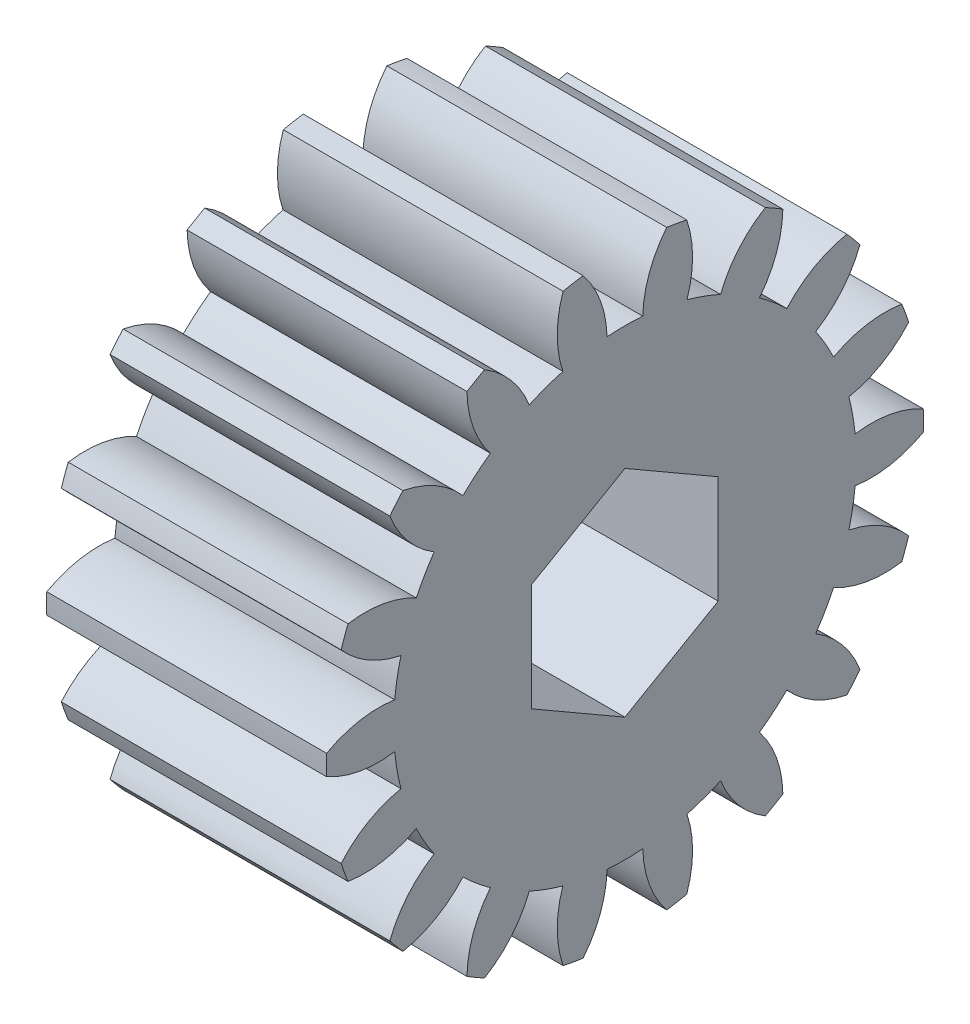
SolidWorks part; units mm, degrees
ref_plane "Plane1" through (0, 0, 0) normal (0, 0, 1) x (1, 0, 0)
ref_plane "Plane2" through (0, 0, 0) normal (0, 1, 0) x (1, 0, 0)
ref_plane "Plane3" through (0, 0, 0) normal (1, 0, 0) x (0, 0, -1)
other "Configuration Table"
sketch "HoldingSke" plane through (0, 0, 0) normal (0, 1, 0) x (1, 0, 0)
  line L0 (0, 0) -> (1.1888, -0.3863)
  line L1 (-15, 0) -> (100, 0) construction
  line L2 (0, 0) -> (-2.1039, 2.3779)
  line L3 (0, 0) -> (-11.863, 4.5341)
  line L4 (0, 0) -> (8.2133, 2.6687)
  line L5 (0, 0) -> (-46.8476, -17.4728)
  line L6 (0, 0) -> (-6.2172, -4.1948)
  line L7 (-2.1039, 2.3779) -> (8.6586, 51.2059)
  line L8 (-76.2, 54.61) -> (-75.3, 54.61)
  line L9 (-67.7845, 28.3722) -> (-49.3413, 33.142)
  line L10 (-76.2, 71.12) -> (104.1128, 71.12)
  line L11 (0, 0) -> (-7.5, 0)
  line L12 (-76.2, 101.6) -> (-76.17, 101.6)
  line L13 (24.9733, 27.94) -> (52.9518, 28.4284)
  line L14 (24.9733, 27.94) -> (24.9743, 27.94)
  line L15 (24.9733, 27.94) -> (100.4006, 29.5858)
  line L16 (-63.627, -0.8) -> (-12.827, -0.8)
  circle A0 centre (0, 0) radius 2.5
  circle A1 centre (0, 0) radius 6.199
  circle A2 centre (0, 0) radius 37.5
  circle A3 centre (0, 0) radius 2.5
  dimension "MHD" = 12.398
  dimension "Hub_dia" = 75
  dimension "Bore" = 5
  dimension "MBD" = 5
  dimension "Num_teeth" = 18
  dimension "Pitch" = 1.25
  dimension "Overall_len" = 50
  dimension "Show_teeth" = 18
  dimension "Thickness" = 7.5
  dimension "OAL" = 50.0001
  dimension "T_dim" = 0.9
  dimension "Ap" = 14.5
  dimension "H" = 19.05
  dimension "Pitch_radius" = 180.3128
  dimension "Width" = 7.5
  dimension "Backlash" = 0.03
  dimension "Addendum_fac" = 1
  dimension "Dedendum_fac" = 1.25
  dimension "Clearance_fac" = 0.25
  dimension "Dedendum_add" = 0.001
  dimension "Module" = 0.8
sketch "BasProSke" plane through (0, 0, 0) normal (0, 1, 0) x (1, 0, 0)
  line L0 (-10, 0) -> (60, 0) construction
  line L1 (0, 0) -> (0, 8)
  line L2 (0, 0) -> (7.5, 0)
  line L3 (7.5, 0) -> (7.5, 8)
  line L4 (7.5, 8) -> (0, 8)
  dimension "Thickness" = 7.5
  dimension "Diameter" = 16
revolve "Base-Revolve" add sketch "BasProSke" angle 360 about L0
sketch "TooCutSke" plane through (0, 0, 0) normal (1, 0, 0) x (0, 0, -1)
  line L1 (0, 0) -> (0, 107) construction
  line L2 (0, 0) -> (-0.68, 7.1678) construction
  line L3 (0, 0) -> (-2.4925, 14.1359) construction
  line L4 (-0.68, 7.1678) -> (-1.2463, 7.068) construction
  arc A0 (0.479, 6.1805) -> (-0.479, 6.1805) centre (0, 0) ccw
  arc A1 (1.1389, 7.9442) -> (-1.1389, 7.9442) centre (0, 0) ccw
  circle A2 centre (0, 0) radius 7.2 construction
  circle A3 centre (0, 0) radius 6.9707 construction
  arc A4 (-0.479, 6.1805) -> (-1.1389, 7.9442) centre (-3.3581, 6.1085) ccw
  arc A5 (1.1389, 7.9442) -> (0.479, 6.1805) centre (3.3581, 6.1085) ccw
  dimension "Root_dia" = 12.398
  dimension "Overcut_dia" = 16.0508
  dimension "Pitch_dia" = 14.4
  dimension "Base_dia" = 13.9413
  dimension "Flank_rad" = 2.88
  dimension "Half_ang" = 10
  dimension "Half_CT" = 0.575
extrude "ToothCut" cut sketch "TooCutSke" along normal through all
fillet "Breaks" [suppressed] radius 0.016
fillet "RootFillets" [suppressed] radius 0.201
pattern_circular "TeethCuts" count 18 every 20 about axis through (-10, 0, 0) along (1, 0, 0) of "ToothCut", "RootFillets", "Breaks"
sketch "HubNeaOneSke" plane through (0, 0, 0) normal (-1, 0, 0) x (0, 0, 1)
  circle A0 centre (0, 0) radius 6.199
  dimension "Diameter" = 12.398
extrude "HubNearOne" [suppressed] add sketch "HubNeaOneSke" along normal blind 42.5001
sketch "HubNeaBotSke" plane through (0, 0, 0) normal (-1, 0, 0) x (0, 0, 1)
  circle A0 centre (0, 0) radius 6.199
  dimension "Diameter" = 12.398
extrude "HubNearBoth" [suppressed] add sketch "HubNeaBotSke" along normal blind 21.25
ref_plane "FarPln" through (7.5, 0, 0) normal (1, 0, 0) x (0, 0, -1)
sketch "HubFarSke" plane through (7.5, 0, 0) normal (1, 0, 0) x (0, 0, -1)
  circle A0 centre (0, 0) radius 6.199
  dimension "Diameter" = 12.398
extrude "HubFar" [suppressed] add sketch "HubFarSke" along normal blind 21.25
sketch "BorSke" plane through (0, 0, 0) normal (1, 0, 0) x (0, 0, -1)
  circle A0 centre (0, 0) radius 2.5
  dimension "Diameter" = 5
extrude "Bore" cut sketch "BorSke" along normal mid plane 100.0001
sketch "KeySke" plane through (0, 0, 0) normal (1, 0, 0) x (0, 0, -1)
  line L0 (-1, 0) -> (-1, 3.4)
  line L1 (-1, 3.4) -> (1, 3.4)
  line L2 (1, 3.4) -> (1, 0)
  line L3 (0, 0) -> (0, 34) construction
  line L4 (-1, 0) -> (1, 0)
  dimension "Offset" = 3.4
  dimension "Width" = 2
extrude "Keyway" [suppressed] cut sketch "KeySke" along normal mid plane 100.0001
pattern_circular "Keyway2" [suppressed] count 2 every 90 about axis through (-10, 0, 0) along (1, 0, 0)
sketch "Schizzo2" plane through (7.5, 0, 0) normal (1, 0, 0) x (0, 0, -1)
  line L1 (0, 2.8868) -> (-2.5, 1.4434)
  line L2 (-2.5, 1.4434) -> (-2.5, -1.4434)
  line L3 (-2.5, -1.4434) -> (0, -2.8868)
  line L4 (0, -2.8868) -> (2.5, -1.4434)
  line L5 (2.5, -1.4434) -> (2.5, 1.4434)
  line L6 (2.5, 1.4434) -> (0, 2.8868)
  circle A0 centre (0, 0) radius 2.5 construction
extrude "Taglio-Estrusione1" cut sketch "Schizzo2" against normal blind 10
equation "' \"Module@HoldingSke\" = 6.35"
equation "' \"Num_teeth@HoldingSke\" = 12"
equation "' \"Ap@HoldingSke\" =  20"
equation "' \"Ap@HoldingSke\" = 20"
equation "' \"Width@HoldingSke\" = 0.5 * 25.4"
equation "' \"Hub_dia@HoldingSke\"= 1 * 25.4"
equation "' \"Hub_dia@HoldingSke\" = 1 * 25.4"
equation "' \"Overall_len@HoldingSke\" = 1.0 * 25.4"
equation "' \"Bore@HoldingSke\" = 0.75 * 25.4"
equation "' \"T_dim@HoldingSke\" = 0.1 * 25.4"
equation "' \"Width@KeySke\" = 0.25 * 25.4"
equation "' \"Show_teeth@HoldingSke\" = 13"
equation "' \"Backlash@HoldingSke\" = 0.009 * 25.4"
equation "' \"Addendum_fac@HoldingSke\" = 1.0"
equation "' \"Dedendum_fac@HoldingSke\" = 1.25"
equation "' \"Dedendum_add@HoldingSke\" = 0.00005 * 25.4"
equation "' \"Clearance_fac@HoldingSke\" = 0.25"
equation "\"Pitch@HoldingSke\" = 1 / \"Module@HoldingSke\""
equation "\"Overcut_dia@TooCutSke\" = (\"Num_teeth@HoldingSke\" + 2 * \"Addendum_fac@HoldingSke\") / \"Pitch@HoldingSke\" + 0.002 * 25.4"
equation "\"Pitch_dia@TooCutSke\" = \"Num_teeth@HoldingSke\" / \"Pitch@HoldingSke\""
equation "\"Base_dia@TooCutSke\" = \"Num_teeth@HoldingSke\" / \"Pitch@HoldingSke\" * cos((\"Ap@HoldingSke\"  * 3.14159265 / 180))"
equation "\"Root_dia@TooCutSke\" = (\"Num_teeth@HoldingSke\" + 2) / \"Pitch@HoldingSke\" - 2 * (\"Addendum_fac@HoldingSke\" + \"Dedendum_fac@HoldingSke\") / \"Pitch@HoldingSke\" - \"Dedendum_add@HoldingSke\" * 2"
equation "\"Half_ang@TooCutSke\" = 180 / \"Num_teeth@HoldingSke\""
equation "\"Half_CT@TooCutSke\" = \"Num_teeth@HoldingSke\" / \"Pitch@HoldingSke\" * sin((3.14159265 / 2 / \"Num_teeth@HoldingSke\")) / 2 - 7 * \"Backlash@HoldingSke\" / 4"
equation "\"Flank_rad@TooCutSke\" = \"Num_teeth@HoldingSke\" / \"Pitch@HoldingSke\" / 5"
equation "\"Radius@RootFillets\" = \"Clearance_fac@HoldingSke\" / \"Pitch@HoldingSke\" + \"Dedendum_add@HoldingSke\""
equation "\"Break_rad@Breaks\" = 0.02 / \"Pitch@HoldingSke\""
equation "\"Thickness@HoldingSke\" = \"Width@HoldingSke\""
equation "\"OAL@HoldingSke\" = \"Thickness@HoldingSke\""
equation "\"MHD@HoldingSke\" = (\"Num_teeth@HoldingSke\" + 2) / \"Pitch@HoldingSke\" - 2 * (\"Addendum_fac@HoldingSke\" + \"Dedendum_fac@HoldingSke\")  / \"Pitch@HoldingSke\" - \"Dedendum_add@HoldingSke\" * 2"
equation "\"MBD@HoldingSke\" = (\"Num_teeth@HoldingSke\" + 2) / \"Pitch@HoldingSke\" - 2 * (\"Addendum_fac@HoldingSke\" + \"Dedendum_fac@HoldingSke\")  / \"Pitch@HoldingSke\" - \"Dedendum_add@HoldingSke\" * 2 - 0.002 * 25.4"
equation "\"MHD@HoldingSke\" = ((sgn( \"MHD@HoldingSke\" - \"Hub_dia@HoldingSke\" )-1)*( \"MHD@HoldingSke\" - \"Hub_dia@HoldingSke\" ))/-2+ \"Hub_dia@HoldingSke\""
equation "\"MBD@HoldingSke\" = ((sgn( \"MBD@HoldingSke\" - \"Bore@HoldingSke\" )-1)*( \"MBD@HoldingSke\" - \"Bore@HoldingSke\" ))/-2+ \"Bore@HoldingSke\""
equation "\"OAL@HoldingSke\" = ((sgn( \"OAL@HoldingSke\" - \"Overall_len@HoldingSke\" )+1)*( \"OAL@HoldingSke\" - \"Overall_len@HoldingSke\" ))/2 + \"Overall_len@HoldingSke\" + 0.000002 * 25.4"
equation "\"Num_teeth@TeethCuts\" = int( \"Show_teeth@HoldingSke\" ) + 1"
equation "\"Num_teeth@TeethCuts\" = ((sgn( \"Num_teeth@TeethCuts\" - \"Num_teeth@HoldingSke\" )-1)*( \"Num_teeth@TeethCuts\" - \"Num_teeth@HoldingSke\" ))/-2+ \"Num_teeth@HoldingSke\""
equation "\"Num_teeth@TeethCuts\" = ((sgn( \"Num_teeth@TeethCuts\" - 2.0)+1)*( \"Num_teeth@TeethCuts\" - 2.0))/2 +2.0"
equation "\"Angle@TeethCuts\" = 360.0 / \"Num_teeth@HoldingSke\""
equation "\"Diameter@BasProSke\" = (\"Num_teeth@HoldingSke\" + 2 * \"Addendum_fac@HoldingSke\") / \"Pitch@HoldingSke\""
equation "\"Thickness@BasProSke\"  = \"Thickness@HoldingSke\""
equation "' \"Fillet_rad@BasProSke\" =  \"Thickness@HoldingSke\" * 0.05"
equation "' \"Fillet_rad@BasProSke\" = \"Thickness@HoldingSke\" * 0.05"
equation "\"MHD@HoldingSke\" = ((sgn( \"MHD@HoldingSke\" - \"Root_dia@TooCutSke\" )-1)*( \"MHD@HoldingSke\" - \"Root_dia@TooCutSke\" ))/-2+ \"Root_dia@TooCutSke\""
equation "\"Diameter@HubNeaOneSke\" = \"MHD@HoldingSke\""
equation "\"Length@HubNearOne\" = \"OAL@HoldingSke\" - \"Thickness@BasProSke\""
equation "\"Diameter@HubNeaBotSke\" = \"MHD@HoldingSke\""
equation "\"Length@HubNearBoth\" = ( \"OAL@HoldingSke\" - \"Thickness@BasProSke\" ) / 2.0"
equation "\"Thickness@FarPln\" = \"Thickness@BasProSke\""
equation "\"Diameter@HubFarSke\" = \"MHD@HoldingSke\""
equation "\"Length@HubFar\" = ( \"OAL@HoldingSke\" - \"Thickness@BasProSke\" ) / 2.0"
equation "\"Diameter@BorSke\" = \"MBD@HoldingSke\""
equation "\"D1@Bore\" = \"OAL@HoldingSke\" * 2.0"
equation "\"D1@Keyway\" = \"OAL@HoldingSke\" * 2.0"
equation "\"Offset@KeySke\" = \"T_dim@HoldingSke\" + \"MBD@HoldingSke\" / 2.0"
